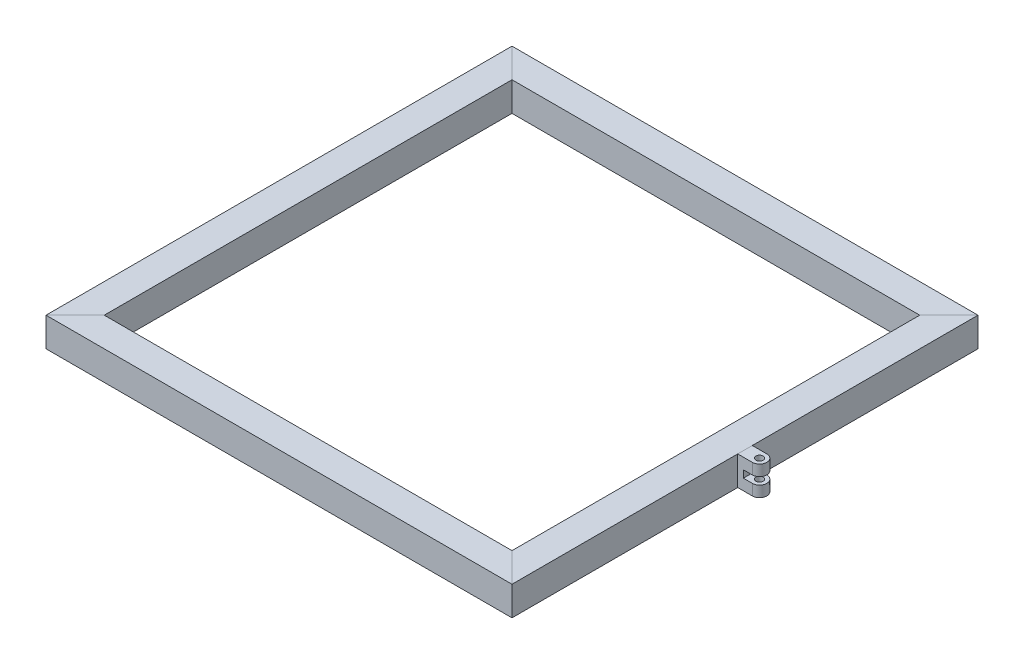
SolidWorks part; units mm, degrees
material "AISI 1020"
ref_plane "Alzado" through (0, 0, 0) normal (0, 0, 1) x (1, 0, 0)
ref_plane "Planta" through (0, 0, 0) normal (0, 1, 0) x (1, 0, 0)
ref_plane "Vista lateral" through (0, 0, 0) normal (1, 0, 0) x (0, 0, -1)
sketch "Croquis1" plane through (0, 0, 0) normal (0, 1, 0) x (1, 0, 0)
  line L1 (-150, 150) -> (150, 150)
  line L2 (-150, 150) -> (-150, -150)
  line L3 (-150, -150) -> (150, -150)
  line L4 (150, 150) -> (150, -150)
  line L5 (-150, 150) -> (150, -150) construction
  line L6 (-150, -150) -> (150, 150) construction
  point P0 (0, 0)
  dimension "D1" = 300
  dimension "D2" = 300
other "Tubo cuadrado 20 X 20 X 2(2)"
ref_plane "Plano2" through (-150, 0, -150) normal (0, 0, 1) x (1, 0, 0)
sketch "Sketch1" plane through (-150, 0, -150) normal (0, 0, 1) x (1, 0, 0)
  line L2 (10, 10) -> (-10, 10)
  line L3 (10, 10) -> (10, -10)
  line L4 (10, -10) -> (-10, -10)
  line L5 (-10, 10) -> (-10, -10)
  line L6 (10, 10) -> (-10, -10) construction
  line L7 (10, -10) -> (-10, 10) construction
  line L8 (-8, 8) -> (8, 8)
  line L9 (-8, 8) -> (-8, -8)
  line L10 (-8, -8) -> (8, -8)
  line L11 (8, 8) -> (8, -8)
  line L12 (-8, 8) -> (8, -8) construction
  line L13 (-8, -8) -> (8, 8) construction
  point P0 (0, 0)
  point P5 (0, 0)
  dimension "D1" = 20
  dimension "D2" = 20
  dimension "D3" = 2
sketch "Croquis4" plane through (0, -10, 0) normal (0, -1, 0) x (1, 0, 0)
  line L0 (0, 0) -> (0, 150) construction
  line L1 (0, 150) -> (-85.4, 150) construction
  line L2 (-82.3874, 0) -> (96.4647, 0) construction
  circle A0 centre (-85.4, 150) radius 1.2
  circle A1 centre (85.4, 150) radius 1.2
  circle A2 centre (85.4, -150) radius 1.2
  circle A3 centre (-85.4, -150) radius 1.2
  dimension "D1" = 2.4
  dimension "D2" = 85.4
  dimension "D3" = 150
sketch "Croquis6" plane through (160, 0, 0) normal (1, 0, 0) x (0, 0, -1)
  line L0 (0, 0) -> (53.3116, 0) construction
  point P3 (53.3116, 0)
  point P6 (0, 0)
sketch "Croquis7" plane through (0, 10, 0) normal (0, 1, 0) x (1, 0, 0)
  line L0 (-82.3874, 0) -> (160, 0) construction
  line L1 (160, 160) -> (160, -160) construction
  line L2 (160, 0) -> (160, 5)
  line L3 (160, 5) -> (170, 5)
  line L4 (170, -5) -> (160, -5)
  line L5 (160, 0) -> (160, -5)
  arc A2 (170, 5) -> (170, -5) centre (170, 0) cw
  circle A3 centre (170, 0) radius 2.5
  dimension "D3" = 5
  dimension "D5" = 5
  dimension "D1" = 5
  dimension "D2" = 5
  dimension "D4" = 10
extrude "Saliente-Extruir1" add sketch "Croquis7" against normal up to surface (20 mm away) separate body up to face at (150, -10, 0)
sketch "Croquis8" plane through (0, 0, 5) normal (0, 0, 1) x (1, 0, 0)
  line L0 (160, 0) -> (160, 2.5) construction
  line L1 (160, -10) -> (160, 10) construction
  line L2 (160, 2.5) -> (163.8552, 2.5) construction
  line L3 (163.8552, 2.5) -> (178.9608, 2.5)
  line L4 (178.9608, 2.5) -> (178.9608, -2.5)
  line L5 (178.9608, -2.5) -> (163.8552, -2.5)
  line L6 (163.8552, -2.5) -> (160, -2.5) construction
  line L7 (160, 10) -> (160, -10) construction
  line L8 (160, -2.5) -> (160, 0) construction
  line L9 (163.8552, 2.5) -> (163.8552, -2.5)
  line L10 (160, -10) -> (160, 10) construction
  point P4 (0, 0)
  point P12 (0, 0)
  dimension "D1" = 2.5
  dimension "D2" = 2.5
  dimension "D3" = 10
extrude "Cortar-Extruir1" cut sketch "Croquis8" against normal blind 80 contours L3 L4 L5 L9
